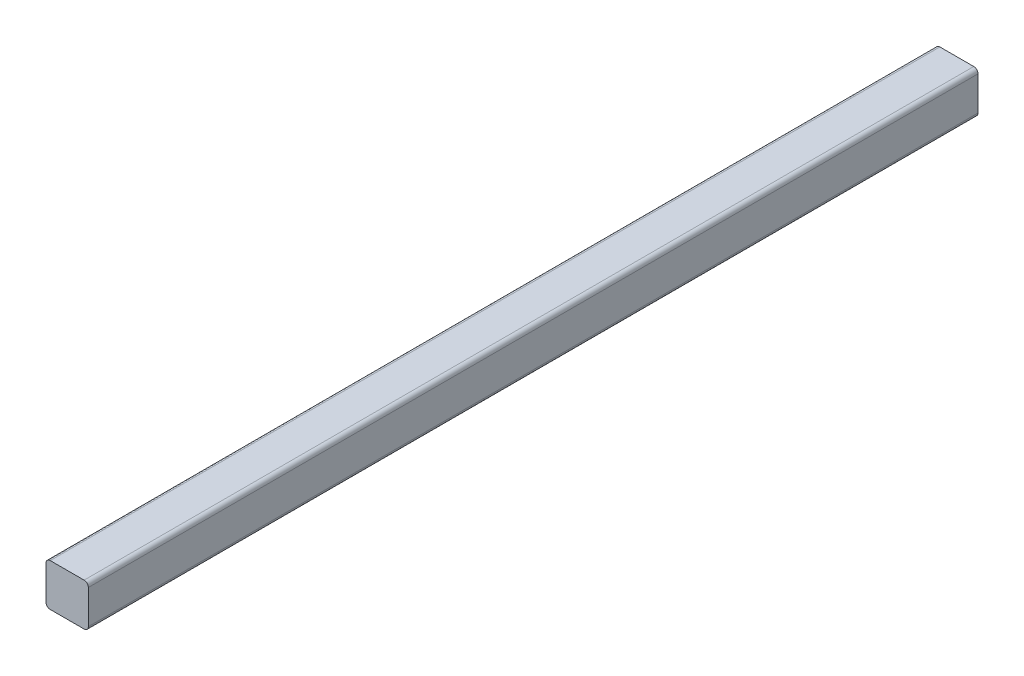
SolidWorks part; units mm, degrees
material "ABS"
ref_plane "Front Plane" through (0, 0, 0) normal (0, 0, 1) x (1, 0, 0)
ref_plane "Top Plane" through (0, 0, 0) normal (0, 1, 0) x (1, 0, 0)
ref_plane "Right Plane" through (0, 0, 0) normal (1, 0, 0) x (0, 0, -1)
sketch "Sketch1" plane through (0, 0, 0) normal (0, 0, 1) x (1, 0, 0)
  line L1 (-2.5, 2.5) -> (2.5, 2.5)
  line L2 (-2.5, 2.5) -> (-2.5, -2.5)
  line L3 (-2.5, -2.5) -> (2.5, -2.5)
  line L4 (2.5, 2.5) -> (2.5, -2.5)
  line L5 (-2.5, 2.5) -> (2.5, -2.5) construction
  line L6 (-2.5, -2.5) -> (2.5, 2.5) construction
  point P0 (0, 0)
  dimension "D1" = 5
extrude "Boss-Extrude1" add sketch "Sketch1" against normal blind 105
fillet "Fillet1" radius 0.5 4 edges at (2.5, -2.5, -52.5) (-2.5, -2.5, -52.5) (-2.5, 2.5, -52.5) (2.5, 2.5, -52.5)
